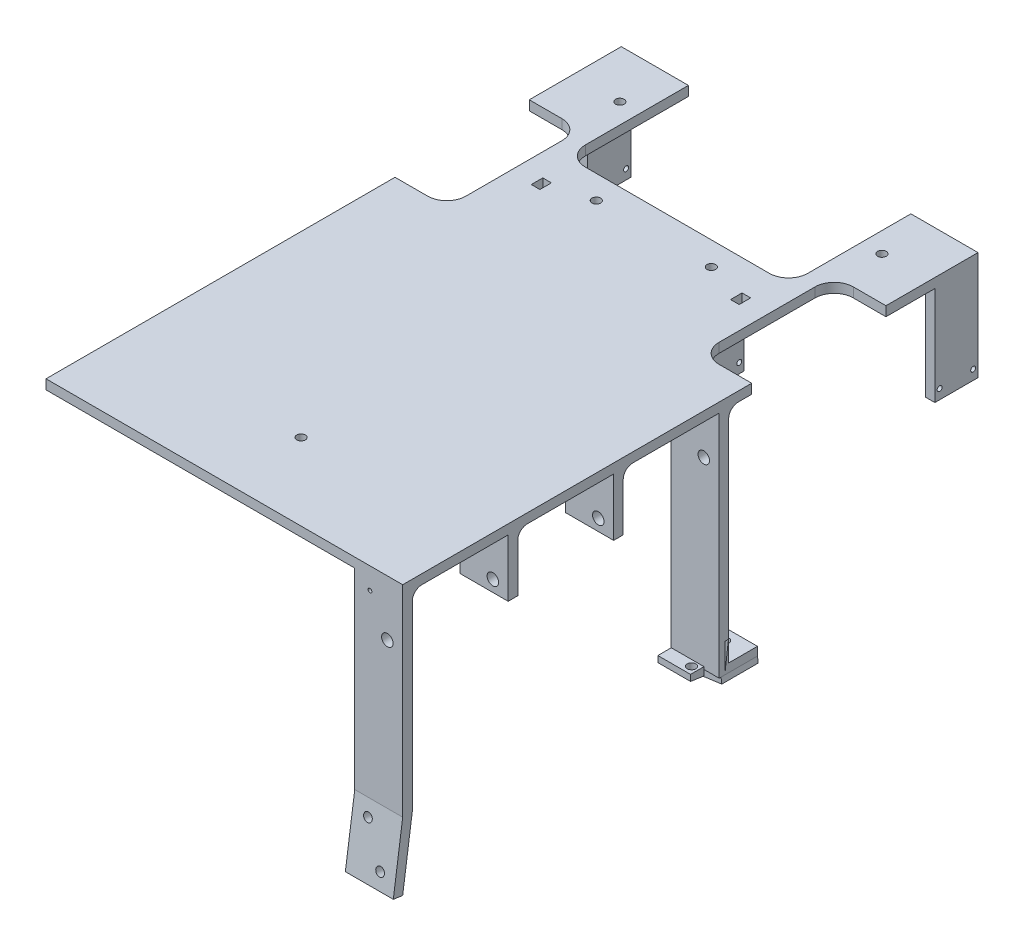
SolidWorks part; units mm, degrees
ref_plane "Front Plane" through (0, 0, 0) normal (0, 0, 1) x (1, 0, 0)
ref_plane "Top Plane" through (0, 0, 0) normal (0, 1, 0) x (1, 0, 0)
ref_plane "Right Plane" through (0, 0, 0) normal (1, 0, 0) x (0, 0, -1)
sketch "Sketch1" plane through (0, 0, 0) normal (0, 1, 0) x (1, 0, 0)
  line L0 (0, 0) -> (0, -300)
  line L1 (0, -300) -> (186, -300)
  line L2 (186, -300) -> (186, 0)
  line L3 (186, 0) -> (176, 0)
  line L4 (176, 0) -> (151, 0)
  line L5 (151, 0) -> (151, -56.1159)
  line L6 (151, -56.1159) -> (35, -56.1159)
  line L7 (35, -56.1159) -> (35, 0)
  line L8 (35, 0) -> (10, 0)
  line L9 (10, 0) -> (0, 0)
  line L10 (93, -300) -> (93, -56.1159) construction
  point P9 (93, -56.1159)
  dimension "D1" = 300
  dimension "D2" = 10
  dimension "D3" = 186
  dimension "D5" = 10
  dimension "D6" = 35
extrude "Boss-Extrude1" add sketch "Sketch1" along normal blind 5
sketch "Sketch2" plane through (0, 0, 0) normal (0, -1, 0) x (1, 0, 0)
  line L1 (50.5, 94) -> (55.5, 94)
  line L2 (50.5, 94) -> (50.5, 71.5)
  line L3 (50.5, 71.5) -> (55.5, 71.5)
  line L4 (55.5, 94) -> (55.5, 71.5)
  line L6 (135.5, 94) -> (130.5, 94)
  line L7 (135.5, 94) -> (135.5, 71.5)
  line L8 (135.5, 71.5) -> (130.5, 71.5)
  line L9 (130.5, 94) -> (130.5, 71.5)
  line L10 (0, 300) -> (186, 300) construction
  line L11 (186, 300) -> (186, 0) construction
  line L12 (0, 0) -> (0, 300) construction
  dimension "D1" = 5
  dimension "D2" = 22.5
  dimension "D3" = 5
  dimension "D4" = 206
  dimension "D5" = 22.5
  dimension "D6" = 50.5
  dimension "D7" = 50.5
extrude "Boss-Extrude2" add sketch "Sketch2" along normal blind 38
sketch "Sketch5" plane through (0, 0, 0) normal (0, -1, 0) x (1, 0, 0)
  line L0 (186, 300) -> (186, 0) construction
  line L1 (186, 295) -> (161, 295)
  line L2 (186, 295) -> (186, 300)
  line L3 (186, 300) -> (161, 300)
  line L4 (161, 295) -> (161, 300)
  line L5 (0, 300) -> (186, 300) construction
  line L6 (186, 240) -> (161, 240)
  line L7 (186, 240) -> (186, 245)
  line L8 (186, 245) -> (161, 245)
  line L9 (161, 240) -> (161, 245)
  line L10 (186, 185) -> (161, 185)
  line L11 (186, 185) -> (186, 190)
  line L12 (186, 190) -> (161, 190)
  line L13 (161, 185) -> (161, 190)
  line L14 (186, 130) -> (161, 130)
  line L15 (186, 130) -> (186, 135)
  line L16 (186, 135) -> (161, 135)
  line L17 (161, 130) -> (161, 135)
  dimension "D1" = 5
  dimension "D2" = 5
  dimension "D3" = 5
  dimension "D4" = 5
  dimension "D5" = 50
  dimension "D6" = 50
  dimension "D7" = 50
  dimension "D8" = 25
extrude "Boss-Extrude3" add sketch "Sketch5" along normal blind 30
fillet "Fillet3" radius 5 4 edges at (173.5, 0, 130) (173.5, 0, 185) (173.5, 0, 240) (173.5, 0, 295)
sketch "Sketch6" plane through (0, 0, 300) normal (0, 0, 1) x (1, 0, 0)
  line L0 (186, -30) -> (161, -30) construction
  line L1 (186, 5) -> (186, -30) construction
  circle A0 centre (178, -24) radius 3
  dimension "D1" = 6
  dimension "D2" = 6
  dimension "D3" = 8
extrude "Cut-Extrude4" cut sketch "Sketch6" against normal blind 172
sketch "Sketch7" plane through (0, 0, 0) normal (0, -1, 0) x (1, 0, 0)
  line L0 (0, 0) -> (0, 300) construction
  line L1 (0, 22.5) -> (5, 22.5)
  line L2 (0, 22.5) -> (0, 0)
  line L3 (0, 0) -> (5, 0)
  line L4 (5, 22.5) -> (5, 0)
  line L5 (186, 125) -> (186, 0) construction
  line L6 (186, 22.5) -> (181, 22.5)
  line L7 (186, 22.5) -> (186, 0)
  line L8 (186, 0) -> (181, 0)
  line L9 (181, 22.5) -> (181, 0)
  line L10 (186, 0) -> (151, 0) construction
  dimension "D1" = 5
  dimension "D2" = 5
  dimension "D3" = 22.5
  dimension "D4" = 22.5
extrude "Boss-Extrude4" add sketch "Sketch7" along normal blind 51.5
sketch "Sketch3" plane through (186, 0, 0) normal (1, 0, 0) x (0, 0, -1)
  line L4 (-71.5, 0) -> (-94, 0)
  line L5 (-71.5, -38) -> (-71.5, 0)
  line L6 (-94, -38) -> (-71.5, -38)
  line L7 (-94, 0) -> (-94, -38)
  line L9 (-71.5, -38) -> (-71.5, 0)
  line L10 (-94, -38) -> (-71.5, -38)
  line L11 (-94, 0) -> (-94, -38)
  line L13 (-71.5, 0) -> (-94, 0)
  circle A0 centre (-74, -32.9) radius 1.3 construction
  circle A1 centre (-91.5, -32.9) radius 1.3 construction
  circle A2 centre (-74, -32.9) radius 1.3
  circle A3 centre (-91.5, -32.9) radius 1.3
  circle A4 centre (-20, -46.4) radius 1.3 construction
  circle A5 centre (-2.5, -46.4) radius 1.3 construction
  circle A6 centre (-20, -46.4) radius 1.3
  circle A7 centre (-2.5, -46.4) radius 1.3
  dimension "D1" = 0
extrude "Cut-Extrude2" cut sketch "Sketch3" against normal through all contours A3 | A2 | A6 | A7
sketch "Sketch9" plane through (0, 0, 0) normal (0, -1, 0) x (1, 0, 0)
  line L0 (35, 0) -> (5, 0) construction
  line L1 (35, 0) -> (151, 0)
  line L2 (35, 0) -> (35, 63.7796)
  line L3 (35, 63.7796) -> (151, 63.7796)
  line L4 (151, 0) -> (151, 63.7796)
  line L5 (35, 56.1159) -> (35, 0) construction
  line L6 (151, 0) -> (151, 56.1159) construction
extrude "Cut-Extrude6" cut sketch "Sketch9" against normal blind 10
sketch "Sketch10" plane through (0, -30, 0) normal (0, -1, 0) x (1, 0, 0)
  line L1 (186, 295) -> (161, 295)
  line L2 (186, 295) -> (186, 300)
  line L3 (186, 300) -> (161, 300)
  line L4 (161, 295) -> (161, 300)
  line L5 (161, 130) -> (186, 130)
  line L6 (161, 130) -> (161, 135)
  line L7 (161, 135) -> (186, 135)
  line L8 (186, 130) -> (186, 135)
extrude "Boss-Extrude5" add sketch "Sketch10" along normal blind 70
sketch "Sketch11" plane through (186, 0, 0) normal (1, 0, 0) x (0, 0, -1)
  line L0 (-300, -100) -> (-304.9019, -134.6439)
  line L1 (-304.9019, -134.6439) -> (-300, -135.3374)
  line L2 (-300, -135.3374) -> (-295, -100)
  line L3 (-300, -100) -> (-295, -100)
extrude "Boss-Extrude6" add sketch "Sketch11" against normal blind 25
sketch "Sketch12" plane through (0, -100, 0) normal (0, -1, 0) x (1, 0, 0)
  line L1 (161, 130) -> (186, 130)
  line L2 (161, 130) -> (161, 135)
  line L3 (161, 135) -> (186, 135)
  line L4 (186, 130) -> (186, 135)
extrude "Boss-Extrude7" add sketch "Sketch12" along normal blind 19.72
sketch "Sketch13" plane through (0, 0, 130) normal (0, 0, -1) x (-1, 0, 0)
  line L0 (-186, -115.3141) -> (-186, -119.72)
  line L1 (-186, -119.72) -> (-186, -5) construction
  line L2 (-186, -119.72) -> (-161, -123.1352)
  line L3 (-161, -123.1352) -> (-161, -115.3141)
  line L4 (-161, -115.3141) -> (-186, -115.3141)
  line L5 (-161, -119.72) -> (-161, -5) construction
  line L8 (-88.5025, -135.5912) -> (-182.3051, -122.777) construction
extrude "Boss-Extrude8" add sketch "Sketch13" along normal blind 15 and the other way blind 4
sketch "Sketch14" plane through (19.4625, -142.4702, 0) normal (0.1354, -0.9908, 0) x (0.9908, 0.1354, 0)
  line L0 (186.3576, 115) -> (168.0843, 132.0374)
  line L1 (168.0843, 115) -> (142.8521, 115) construction
  line L2 (168.0843, 115) -> (168.0843, 134) construction
  line L3 (168.0843, 132.0374) -> (198.0152, 130.431)
  line L4 (198.0152, 130.431) -> (197.5151, 111.3666)
  line L5 (197.5151, 111.3666) -> (186.3576, 109.6075)
  line L6 (186.3576, 109.6075) -> (186.3576, 115)
extrude "Cut-Extrude7" cut sketch "Sketch14" against normal blind 15
sketch "Sketch15" plane through (0, 39.652, 280.2402) normal (0, 0.1401, 0.9901) x (1, 0, 0)
  line L1 (161, -141.043) -> (161, -176.032) construction
  line L2 (186, -141.043) -> (161, -141.043) construction
  line L3 (186, -141.043) -> (186, -176.032) construction
  line L4 (161, -176.032) -> (186, -176.032) construction
  circle A0 centre (178, -168.032) radius 2.25
  circle A1 centre (169, -149.043) radius 2.25
  dimension "D1" = 4.5
  dimension "D2" = 4.5
  dimension "D3" = 8
  dimension "D4" = 8
  dimension "D5" = 8
  dimension "D6" = 8
extrude "Cut-Extrude8" cut sketch "Sketch15" against normal blind 20
sketch "Sketch16" plane through (0, 0, 0) normal (0, -1, 0) x (1, 0, 0)
  line L1 (166, 272) -> (172, 272)
  line L2 (166, 272) -> (166, 275)
  line L3 (166, 275) -> (172, 275)
  line L4 (172, 272) -> (172, 275)
  line L5 (143.4, 272) -> (137.4, 272)
  line L6 (143.4, 272) -> (143.4, 275)
  line L7 (143.4, 275) -> (137.4, 275)
  line L8 (137.4, 272) -> (137.4, 275)
  line L9 (166, 217) -> (172, 217)
  line L10 (166, 217) -> (166, 220)
  line L11 (166, 220) -> (172, 220)
  line L12 (172, 217) -> (172, 220)
  line L13 (166, 162) -> (172, 162)
  line L14 (166, 162) -> (166, 165)
  line L15 (166, 165) -> (172, 165)
  line L16 (172, 162) -> (172, 165)
  line L17 (137.4, 217) -> (143.4, 217)
  line L18 (137.4, 217) -> (137.4, 220)
  line L19 (137.4, 220) -> (143.4, 220)
  line L20 (143.4, 217) -> (143.4, 220)
  line L21 (137.4, 162) -> (143.4, 162)
  line L22 (137.4, 162) -> (137.4, 165)
  line L23 (137.4, 165) -> (143.4, 165)
  line L24 (143.4, 162) -> (143.4, 165)
  line L25 (186, 180) -> (186, 135) construction
  line L28 (161, 295) -> (186, 295) construction
  line L29 (161, 240) -> (186, 240) construction
  line L30 (161, 185) -> (186, 185) construction
  dimension "D1" = 3
  dimension "D2" = 3
  dimension "D3" = 3
  dimension "D4" = 3
  dimension "D5" = 3
  dimension "D6" = 3
  dimension "D7" = 20
  dimension "D8" = 22.6
  dimension "D9" = 6
  dimension "D10" = 6
  dimension "D11" = 23
  dimension "D12" = 23
  dimension "D13" = 23
extrude "Boss-Extrude9" add sketch "Sketch16" along normal blind 12.4
sketch "Sketch17" plane through (0, 0, 162) normal (0, 0, -1) x (-1, 0, 0)
  arc A0 (-169.75, -6.8) -> (-169.75, -5.6) centre (-168.95, -6.2) ccw construction
  arc A1 (-169.75, -6.8) -> (-169.75, -5.6) centre (-168.95, -6.2) ccw
  circle A2 centre (-168.95, -6.2) radius 1
  circle A3 centre (-140.45, -6.2) radius 1
extrude "Cut-Extrude9" cut sketch "Sketch17" against normal through all contours A1 A2 | A3
sketch "Sketch27" plane through (19.4625, -142.4702, 0) normal (0.1354, -0.9908, 0) x (0.9908, 0.1354, 0)
  line L1 (142.8521, 115) -> (168.0843, 115)
  line L2 (142.8521, 115) -> (142.8521, 134)
  line L3 (142.8521, 134) -> (168.0843, 134)
  line L4 (168.0843, 115) -> (168.0843, 134)
extrude "Boss-Extrude11" add sketch "Sketch27" along normal blind 3
fillet "Fillet4" radius 5 6 edges at (140.4, 0, 275) (169, 0, 275) (140.4, 0, 220) (169, 0, 220) (140.4, 0, 165) (169, 0, 165)
sketch "Sketch18" plane through (0, -115.3141, 0) normal (0, 1, 0) x (1, 0, 0)
  circle A0 centre (174.8857, -120.9947) radius 2.25
  dimension "D1" = 4.5
extrude "Cut-Extrude10" cut sketch "Sketch18" against normal through all
sketch "Sketch19" plane through (0, 0, 0) normal (0, -1, 0) x (1, 0, 0)
  line L0 (42.3, 80.75) -> (39.8, 80.75) construction
  line L1 (39.8, 84.75) -> (39.8, 80.75) construction
  line L2 (42.3, 84.75) -> (42.3, 80.75) construction
  line L3 (39.8, 84.75) -> (42.3, 84.75) construction
  line L4 (42.3, 80.75) -> (39.8, 80.75) construction
  line L5 (39.8, 84.75) -> (39.8, 80.75) construction
  line L6 (42.3, 84.75) -> (42.3, 80.75) construction
  line L7 (39.8, 84.75) -> (42.3, 84.75) construction
  line L8 (143.7, 80.75) -> (143.7, 84.75) construction
  line L9 (143.7, 84.75) -> (146.2, 84.75) construction
  line L10 (146.2, 80.75) -> (146.2, 84.75) construction
  line L11 (146.2, 80.75) -> (143.7, 80.75) construction
  line L12 (143.7, 80.75) -> (143.7, 84.75) construction
  line L13 (143.7, 84.75) -> (146.2, 84.75) construction
  line L14 (146.2, 80.75) -> (146.2, 84.75) construction
  line L15 (146.2, 80.75) -> (143.7, 80.75) construction
  line L16 (43.3, 79.75) -> (38.8, 79.75)
  line L17 (38.8, 85.75) -> (38.8, 79.75)
  line L18 (38.8, 85.75) -> (43.3, 85.75)
  line L19 (43.3, 85.75) -> (43.3, 79.75)
  line L20 (142.7, 79.75) -> (142.7, 85.75)
  line L21 (142.7, 85.75) -> (147.2, 85.75)
  line L22 (147.2, 79.75) -> (147.2, 85.75)
  line L23 (147.2, 79.75) -> (142.7, 79.75)
  line L31 (151, 0) -> (181, 0)
  line L32 (181, 0) -> (181, 22.5)
  line L34 (186, 22.5) -> (186, 125)
  line L35 (186, 125) -> (161, 125)
  line L36 (161, 125) -> (161, 135)
  line L37 (161, 135) -> (186, 135)
  line L38 (186, 135) -> (186, 180)
  line L39 (186, 180) -> (161, 180)
  line L40 (161, 180) -> (161, 190)
  line L41 (161, 190) -> (186, 190)
  line L42 (186, 190) -> (186, 235)
  line L43 (186, 235) -> (161, 235)
  line L44 (161, 235) -> (161, 245)
  line L45 (161, 245) -> (186, 245)
  line L46 (186, 245) -> (186, 290)
  line L47 (186, 290) -> (161, 290)
  line L48 (161, 290) -> (161, 300)
  line L49 (161, 300) -> (0, 300)
  line L50 (0, 300) -> (0, 22.5)
  line L51 (0, 22.5) -> (5, 22.5)
  line L52 (5, 22.5) -> (5, 0)
  line L53 (5, 0) -> (35, 0)
  line L56 (151, 63.7796) -> (151, 0)
  line L57 (151, 63.7796) -> (151, 0)
  line L58 (35, 0) -> (35, 63.7796)
  line L61 (151, 0) -> (181, 0)
  line L64 (186, 22.5) -> (186, 125)
  line L65 (186, 125) -> (161, 125)
  line L66 (161, 125) -> (161, 135)
  line L67 (161, 135) -> (186, 135)
  line L68 (186, 135) -> (186, 180)
  line L69 (186, 180) -> (161, 180)
  line L70 (161, 180) -> (161, 190)
  line L71 (161, 190) -> (186, 190)
  line L72 (186, 190) -> (186, 235)
  line L73 (186, 235) -> (161, 235)
  line L74 (161, 235) -> (161, 245)
  line L75 (161, 245) -> (186, 245)
  line L76 (186, 245) -> (186, 290)
  line L77 (186, 290) -> (161, 290)
  line L78 (161, 290) -> (161, 300)
  line L79 (161, 300) -> (0, 300)
  line L80 (0, 300) -> (0, 22.5)
  line L81 (0, 22.5) -> (5, 22.5)
  line L82 (5, 22.5) -> (5, 0)
  line L83 (5, 0) -> (35, 0)
  line L106 (35, 0) -> (35, 63.7796)
  line L107 (35, 63.7796) -> (151, 63.7796)
  line L108 (35, 63.7796) -> (151, 63.7796)
  line L116 (181, 22.5) -> (186, 22.5)
  line L122 (181, 22.5) -> (186, 22.5)
  line L124 (181, 0) -> (181, 22.5)
  dimension "D1" = 0
  dimension "D2" = 1
  dimension "D3" = 1
extrude "Cut-Extrude12" cut sketch "Sketch19" against normal through all contours L23 L22 L21 L20 | L19 L18 L17 L16
fillet "Fillet6" radius 10 2 edges at (151, 2.5, 63.7796) (35, 2.5, 63.7796)
sketch "Sketch21" plane through (0, 0, 0) normal (0, -1, 0) x (1, 0, 0)
  line L0 (0, 22.5) -> (0, 300) construction
  line L1 (0, 48) -> (27, 48)
  line L2 (0, 48) -> (0, 118)
  line L3 (0, 118) -> (27, 118)
  line L4 (27, 48) -> (27, 118)
  line L5 (186, 125) -> (186, 22.5) construction
  line L6 (186, 48) -> (159, 48)
  line L7 (186, 48) -> (186, 118)
  line L8 (186, 118) -> (159, 118)
  line L9 (159, 48) -> (159, 118)
  line L10 (0, 300) -> (161, 300) construction
  dimension "D1" = 70
  dimension "D2" = 182
  dimension "D3" = 70
  dimension "D4" = 182
  dimension "D5" = 27
  dimension "D6" = 27
extrude "Cut-Extrude14" cut sketch "Sketch21" against normal through all
fillet "Fillet7" radius 10 4 edges at (27, 2.5, 118) (27, 2.5, 48) (159, 2.5, 48) (159, 2.5, 118)
fillet "Fillet8" radius 2.5 2 edges at (55.5, 0, 82.75) (130.5, 0, 82.75)
sketch "Sketch22" plane through (0, 0, 0) normal (0, -1, 0) x (1, 0, 0)
  line L34 (17, 48) -> (0, 48)
  line L35 (0, 48) -> (0, 22.5)
  line L36 (0, 22.5) -> (5, 22.5)
  line L37 (5, 22.5) -> (5, 0)
  line L38 (5, 0) -> (35, 0)
  line L39 (35, 0) -> (35, 53.7796)
  line L40 (45, 63.7796) -> (141, 63.7796)
  line L41 (151, 53.7796) -> (151, 0)
  line L42 (151, 0) -> (181, 0)
  line L43 (181, 0) -> (181, 22.5)
  line L44 (181, 22.5) -> (186, 22.5)
  line L45 (186, 22.5) -> (186, 48)
  line L46 (186, 48) -> (169, 48)
  line L47 (159, 58) -> (159, 108)
  line L48 (169, 118) -> (186, 118)
  line L49 (186, 118) -> (186, 125)
  line L50 (186, 125) -> (161, 125)
  line L51 (161, 125) -> (161, 135)
  line L52 (161, 135) -> (186, 135)
  line L53 (186, 135) -> (186, 180)
  line L54 (186, 180) -> (161, 180)
  line L55 (161, 180) -> (161, 190)
  line L56 (161, 190) -> (186, 190)
  line L57 (186, 190) -> (186, 235)
  line L58 (186, 235) -> (161, 235)
  line L59 (161, 235) -> (161, 245)
  line L60 (161, 245) -> (186, 245)
  line L61 (186, 245) -> (186, 290)
  line L62 (186, 290) -> (161, 290)
  line L63 (161, 290) -> (161, 300)
  line L64 (161, 300) -> (0, 300)
  line L65 (0, 300) -> (0, 118)
  line L66 (0, 118) -> (17, 118)
  line L67 (27, 108) -> (27, 58)
  line L68 (17, 48) -> (0, 48)
  line L69 (0, 48) -> (0, 22.5)
  line L70 (0, 22.5) -> (5, 22.5)
  line L71 (5, 22.5) -> (5, 0)
  line L72 (5, 0) -> (35, 0)
  line L73 (35, 0) -> (35, 53.7796)
  line L74 (45, 63.7796) -> (141, 63.7796)
  line L75 (151, 53.7796) -> (151, 0)
  line L76 (151, 0) -> (181, 0)
  line L77 (181, 0) -> (181, 22.5)
  line L78 (181, 22.5) -> (186, 22.5)
  line L79 (186, 22.5) -> (186, 48)
  line L80 (186, 48) -> (169, 48)
  line L81 (159, 58) -> (159, 108)
  line L82 (169, 118) -> (186, 118)
  line L83 (186, 118) -> (186, 125)
  line L84 (186, 125) -> (161, 125)
  line L85 (161, 125) -> (161, 135)
  line L86 (161, 135) -> (186, 135)
  line L87 (186, 135) -> (186, 180)
  line L88 (186, 180) -> (161, 180)
  line L89 (161, 180) -> (161, 190)
  line L90 (161, 190) -> (186, 190)
  line L91 (186, 190) -> (186, 235)
  line L92 (186, 235) -> (161, 235)
  line L93 (161, 235) -> (161, 245)
  line L94 (161, 245) -> (186, 245)
  line L95 (186, 245) -> (186, 290)
  line L96 (186, 290) -> (161, 290)
  line L97 (161, 290) -> (161, 300)
  line L98 (161, 300) -> (0, 300)
  line L99 (0, 300) -> (0, 118)
  line L100 (0, 118) -> (17, 118)
  line L101 (27, 108) -> (27, 58)
  circle A0 centre (123, 76.0448) radius 2.25 construction
  circle A1 centre (123, 76.0448) radius 2.25
  circle A2 centre (63, 76.0448) radius 2.25 construction
  circle A3 centre (63, 76.0448) radius 2.25
  circle A4 centre (24.5, 25.25) radius 2.25 construction
  circle A5 centre (24.5, 25.25) radius 2.25
  arc A6 (45, 63.7796) -> (35, 53.7796) centre (45, 53.7796) ccw
  arc A7 (151, 53.7796) -> (141, 63.7796) centre (141, 53.7796) ccw
  arc A8 (159, 58) -> (169, 48) centre (169, 58) ccw
  arc A9 (169, 118) -> (159, 108) centre (169, 108) ccw
  arc A10 (27, 108) -> (17, 118) centre (17, 108) ccw
  arc A11 (17, 48) -> (27, 58) centre (17, 58) ccw
  arc A12 (45, 63.7796) -> (35, 53.7796) centre (45, 53.7796) ccw
  arc A13 (151, 53.7796) -> (141, 63.7796) centre (141, 53.7796) ccw
  arc A14 (159, 58) -> (169, 48) centre (169, 58) ccw
  arc A15 (169, 118) -> (159, 108) centre (169, 108) ccw
  arc A16 (27, 108) -> (17, 118) centre (17, 108) ccw
  arc A17 (17, 48) -> (27, 58) centre (17, 58) ccw
  circle A18 centre (161.5, 25.6175) radius 2.25 construction
  circle A19 centre (161.5, 25.6175) radius 2.25
  dimension "D1" = 0
extrude "Cut-Extrude16" cut sketch "Sketch22" against normal blind 10 contours A5 | A3 | A1 | A19
sketch "Sketch23" plane through (0, 0, 135) normal (0, 0, 1) x (1, 0, 0)
  line L1 (178.1063, -118.4368) -> (161.0628, -118.4368)
  line L2 (178.1063, -118.4368) -> (178.1063, -123.5756)
  line L3 (178.1063, -123.5756) -> (161.0628, -123.5756)
  line L4 (161.0628, -118.4368) -> (161.0628, -123.5756)
extrude "Boss-Extrude10" add sketch "Sketch23" along normal blind 7
sketch "Sketch24" plane through (161.0628, 0, 0) normal (-1, 0, 0) x (0, 0, 1)
  line L0 (295, -100) -> (133.6076, -122.8359) construction
  line L1 (142, -121.6484) -> (135, -122.6389)
  line L2 (135, -119.72) -> (135, -123.5756) construction
  line L3 (142, -118.4368) -> (142, -123.5756) construction
  line L4 (142, -121.6484) -> (142, -124.3381)
  line L5 (142, -124.3381) -> (134.715, -124.3381)
  line L6 (134.715, -124.3381) -> (135, -122.6389)
extrude "Cut-Extrude17" cut sketch "Sketch24" against normal up to next
sketch "Sketch25" plane through (0, -118.4368, 0) normal (0, 1, 0) x (1, 0, 0)
  circle A0 centre (174.7191, -138.0894) radius 2.25
  point P2 (174.7191, -138.0894)
  dimension "D1" = 4.5
extrude "Cut-Extrude18" cut sketch "Sketch25" against normal up to next
sketch "Sketch28" plane through (0, 5, 0) normal (0, 1, 0) x (1, 0, 0)
  line L0 (0, -300) -> (186, -300) construction
  circle A0 centre (93, -260) radius 2.25
  point P4 (93, -300)
  dimension "D1" = 4.5
  dimension "D2" = 40
extrude "Cut-Extrude19" cut sketch "Sketch28" against normal through all
